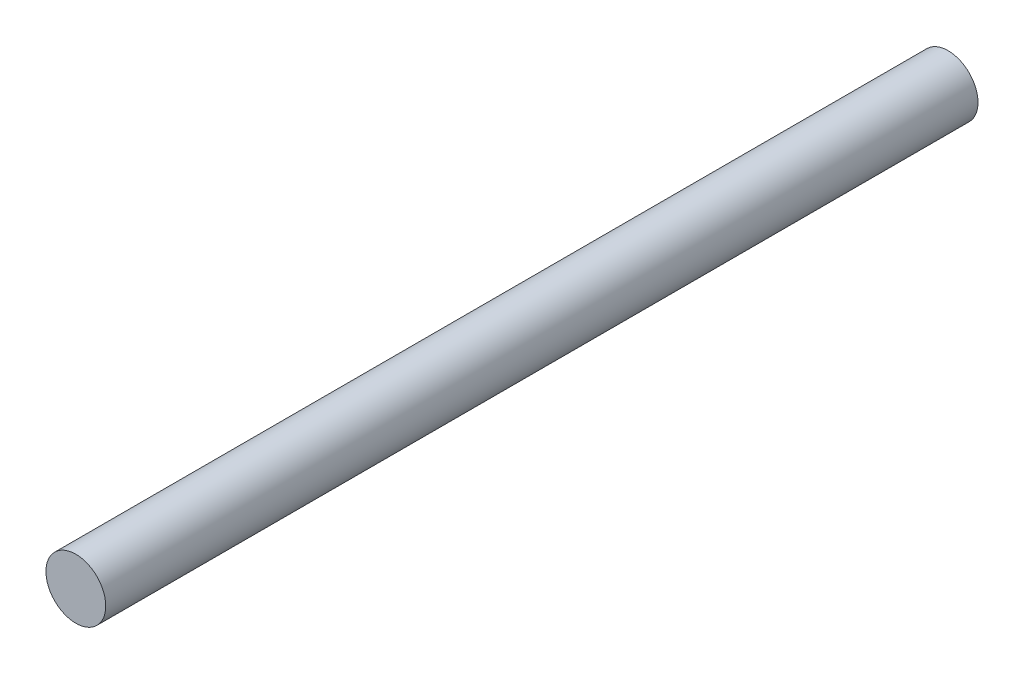
SolidWorks part; units mm, degrees
material "6061-T6 (SS)"
ref_plane "Front Plane" through (0, 0, 0) normal (0, 0, 1) x (1, 0, 0)
ref_plane "Top Plane" through (0, 0, 0) normal (0, 1, 0) x (1, 0, 0)
ref_plane "Right Plane" through (0, 0, 0) normal (1, 0, 0) x (0, 0, -1)
sketch "Sketch1" plane through (0, 0, 0) normal (0, 0, 1) x (1, 0, 0)
  circle A0 centre (0, 0) radius 6
  dimension "D1" = 12
extrude "Boss-Extrude1" add sketch "Sketch1" along normal blind 175
